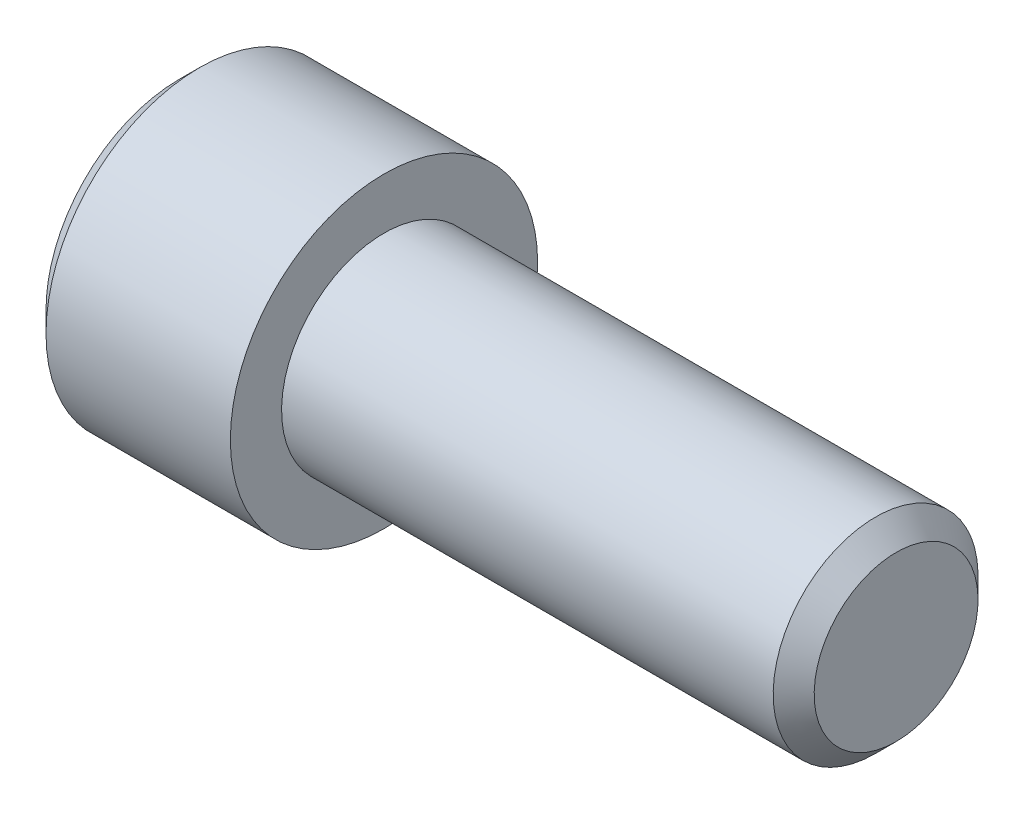
SolidWorks part; units mm, degrees
ref_plane "Front" through (0, 0, 0) normal (0, 0, 1) x (1, 0, 0)
ref_plane "Top" through (0, 0, 0) normal (0, 1, 0) x (1, 0, 0)
ref_plane "Right" through (0, 0, 0) normal (1, 0, 0) x (0, 0, -1)
sketch "Sketch1" plane through (0, 0, 0) normal (0, 0, 1) x (1, 0, 0)
  line L0 (-12, 0) -> (-12, 9)
  line L1 (-12, 0) -> (30, 0)
  line L2 (-12, 9) -> (0, 9)
  line L3 (0, 9) -> (0, 6)
  line L4 (0, 6) -> (30, 6)
  line L6 (30, 6) -> (30, 0)
  line L8 (30, 0) -> (-12, 0) construction
  dimension "D1" = 18
  dimension "D2" = 12
  dimension "D3" = 30
  dimension "D4" = 12
revolve "Revolve1" add sketch "Sketch1" angle 360 about L8
cosmetic thread "Cosmetic Thread1" parameters "D1"=29, "D2"=9.853
sketch "Sketch2" plane through (0, 0, 0) normal (0, 0, 1) x (1, 0, 0)
  line L0 (-12, 0) -> (-12, 4.995)
  line L1 (-12, 4.995) -> (-6, 4.995)
  line L2 (-6, 4.995) -> (-4.6616, 0)
  line L3 (-12, 0) -> (-4.6616, 0)
  line L4 (-4.6616, 0) -> (-12, 0) construction
  line L5 (-12, 9) -> (-12, -9) construction
  dimension "D1" = 9.99
  dimension "D2" = 75
  dimension "D3" = 6
revolve "Cut-Revolve1" cut sketch "Sketch2" angle 360 about L4
sketch "Sketch3" plane through (-12, 0, 0) normal (-1, 0, 0) x (0, 0, 1)
  line L1 (0, -5.7735) -> (5, -2.8868)
  line L2 (5, -2.8868) -> (5, 2.8868)
  line L3 (5, 2.8868) -> (0, 5.7735)
  line L4 (0, 5.7735) -> (-5, 2.8868)
  line L5 (-5, 2.8868) -> (-5, -2.8868)
  line L6 (-5, -2.8868) -> (0, -5.7735)
  circle A1 centre (0, 0) radius 5 construction
  dimension "D1" = 10
extrude "Cut-Extrude1" cut sketch "Sketch3" against normal blind 6
chamfer "Chamfer1" distance 1.2 angle 45 2 edges at (30, -6, 0) (-12, -9, 0)
